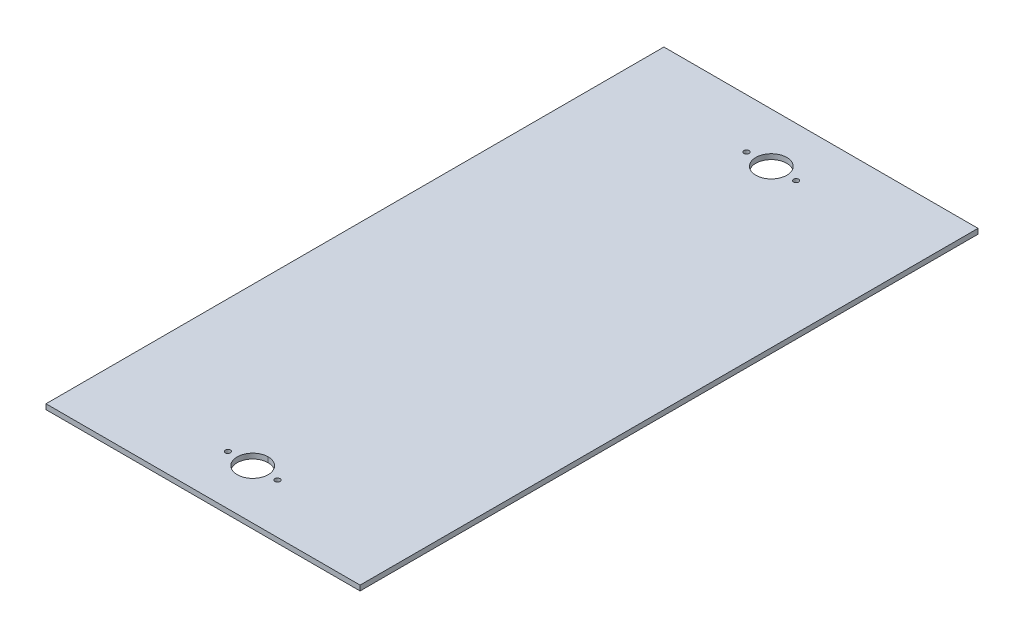
SolidWorks part; units mm, degrees
ref_plane "Front Plane" through (0, 0, 0) normal (0, 0, 1) x (1, 0, 0)
ref_plane "Top Plane" through (0, 0, 0) normal (0, 1, 0) x (1, 0, 0)
ref_plane "Right Plane" through (0, 0, 0) normal (1, 0, 0) x (0, 0, -1)
sketch "Sketch1" plane through (0, 0, 0) normal (0, 1, 0) x (1, 0, 0)
  line L1 (91.8972, 142.6972) -> (-91.8972, 142.6972)
  line L2 (91.8972, 142.6972) -> (91.8972, -142.6972)
  line L3 (91.8972, -142.6972) -> (-91.8972, -142.6972)
  line L4 (-91.8972, 142.6972) -> (-91.8972, -142.6972)
  line L5 (91.8972, 142.6972) -> (-91.8972, -142.6972) construction
  line L6 (91.8972, -142.6972) -> (-91.8972, 142.6972) construction
  point P0 (0, 0)
  dimension "D1" = 183.7944
  dimension "D2" = 285.3944
extrude "Boss-Extrude1" add sketch "Sketch1" along normal blind 2.9972
sketch "Sketch2" plane through (0, 2.9972, 0) normal (0, 1, 0) x (1, 0, 0)
  line L0 (0, -151.7472) -> (0, 151.7472) construction
  line L1 (-91.8972, -142.6972) -> (91.8972, -142.6972)
  line L2 (-91.8972, -142.6972) -> (-91.8972, -180.7972)
  line L3 (-91.8972, -180.7972) -> (91.8972, -180.7972)
  line L4 (91.8972, -142.6972) -> (91.8972, -180.7972)
  line L5 (-91.8972, 142.6972) -> (91.8972, 142.6972)
  line L6 (-91.8972, 142.6972) -> (-91.8972, 180.7972)
  line L7 (-91.8972, 180.7972) -> (91.8972, 180.7972)
  line L8 (91.8972, 142.6972) -> (91.8972, 180.7972)
  line L9 (91.8972, 180.7972) -> (129.9972, 180.7972)
  line L10 (91.8972, 180.7972) -> (91.8972, -180.7972)
  line L11 (91.8972, -180.7972) -> (129.9972, -180.7972)
  line L12 (129.9972, 180.7972) -> (129.9972, -180.7972)
  line L13 (-14.505, 151.7472) -> (14.505, 151.7472) construction
  line L14 (-14.505, -151.7472) -> (14.505, -151.7472) construction
  circle A0 centre (0, 151.7472) radius 7.55 construction
  circle A1 centre (0, -151.7472) radius 7.55 construction
  circle A2 centre (0, -151.7472) radius 9.055
  circle A3 centre (0, 151.7472) radius 9.055
  circle A4 centre (-14.505, 151.7472) radius 1.5
  circle A5 centre (14.505, 151.7472) radius 1.5
  circle A6 centre (-14.505, -151.7472) radius 1.5
  circle A7 centre (14.505, -151.7472) radius 1.5
  point P17 (0, 0)
  point P20 (0, 151.7472)
  point P32 (0, -151.7472)
  line M15 (-91.8972, -142.6972) -> (91.8972, -142.6972)
  line M17 (91.8972, 142.6972) -> (-91.8972, 142.6972)
  dimension "D1" = 15.1
  dimension "D2" = 1.5
  dimension "D6" = 14.505
  dimension "D7" = 3
  dimension "D3" = 38.1
  dimension "D4" = 38.1
  dimension "D5" = 1.505
extrude "Boss-Extrude2" add sketch "Sketch2" against normal up to surface (2.9972 mm away) contours L8 L7 L6 M17 | L4 L2 L3 M15 | L5 A3 | L1 A2
equation "\"wallthickness\"= .118in"
equation "\"floorThickness\"= .220in"
equation "\"D1@Sketch1\"=\"wallthickness\"*2+7in"
equation "\"D2@Sketch1\"=\"wallthickness\"*2+11in"
equation "\"D1@Boss-Extrude1\"=\"wallthickness\""
